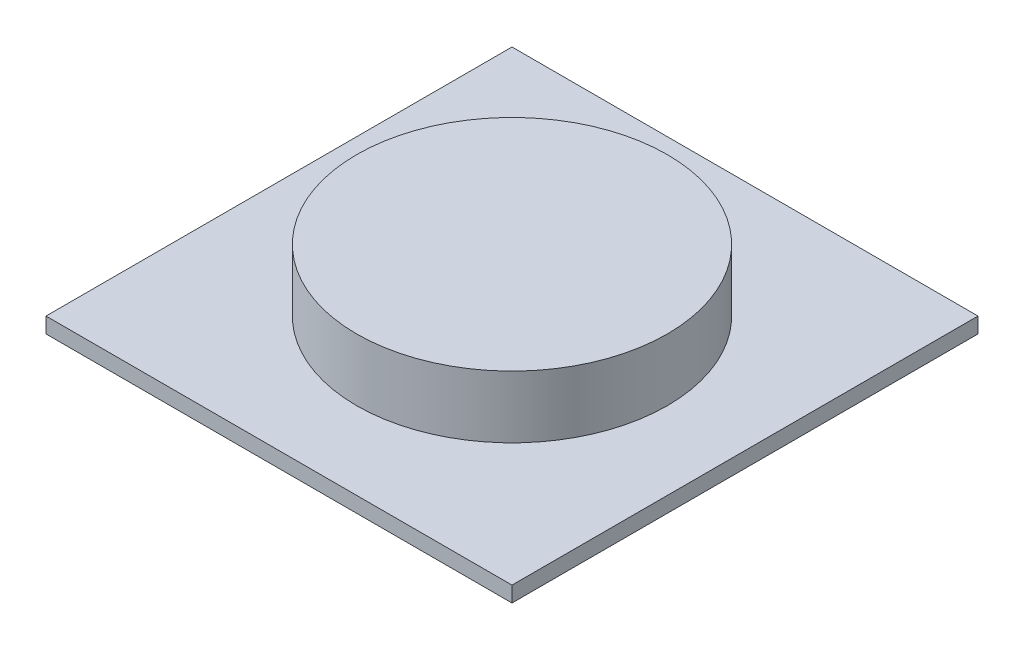
SolidWorks part; units mm, degrees
ref_plane "Front Plane" through (0, 0, 0) normal (0, 0, 1) x (1, 0, 0)
ref_plane "Top Plane" through (0, 0, 0) normal (0, 1, 0) x (1, 0, 0)
ref_plane "Right Plane" through (0, 0, 0) normal (1, 0, 0) x (0, 0, -1)
sketch "Sketch1" plane through (0, 0, 0) normal (0, 1, 0) x (1, 0, 0)
  line L1 (-37.5, -37.5) -> (37.5, -37.5)
  line L2 (-37.5, -37.5) -> (-37.5, 37.5)
  line L3 (-37.5, 37.5) -> (37.5, 37.5)
  line L4 (37.5, -37.5) -> (37.5, 37.5)
  line L5 (-37.5, -37.5) -> (37.5, 37.5) construction
  line L6 (-37.5, 37.5) -> (37.5, -37.5) construction
  point P0 (0, 0)
  dimension "D1" = 75
extrude "Boss-Extrude1" add sketch "Sketch1" along normal blind 2.5
sketch "Sketch2" plane through (0, 2.5, 0) normal (0, 1, 0) x (1, 0, 0)
  circle A0 centre (0, 0) radius 25
  dimension "D1" = 50
extrude "Boss-Extrude2" add sketch "Sketch2" along normal blind 10
